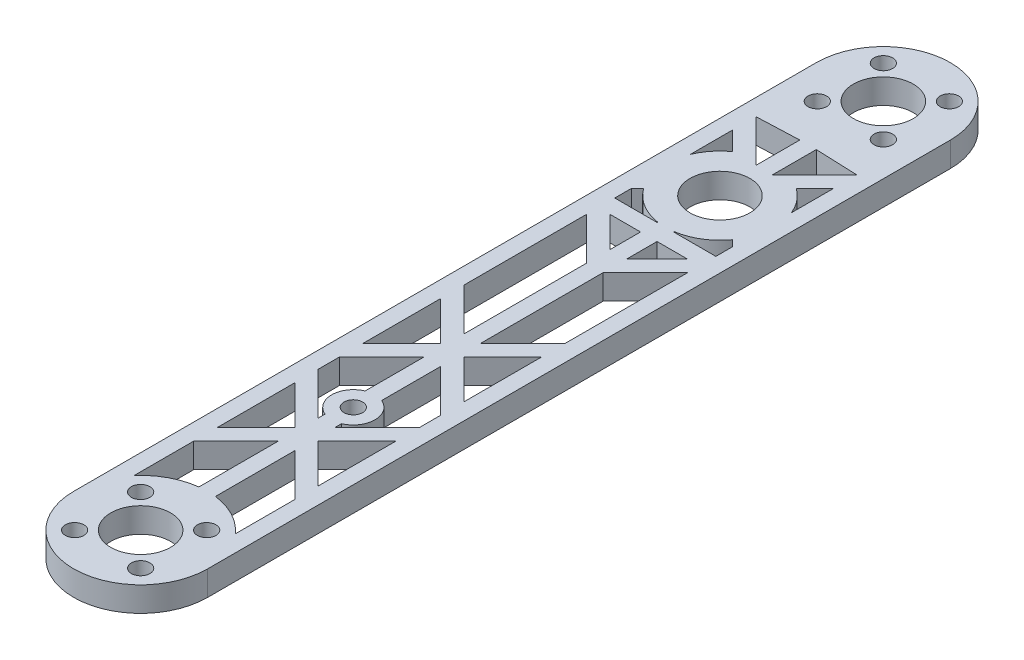
SolidWorks part; units mm, degrees
ref_plane "Front Plane" through (0, 0, 0) normal (0, 0, 1) x (1, 0, 0)
ref_plane "Top Plane" through (0, 0, 0) normal (0, 1, 0) x (1, 0, 0)
ref_plane "Right Plane" through (0, 0, 0) normal (1, 0, 0) x (0, 0, -1)
sketch "Sketch2" plane through (0, 0, 0) normal (0, 1, 0) x (1, 0, 0)
  line L0 (0, 0) -> (-127946.3425, 0) construction
  line L1 (0, 0) -> (0, 127946.3425) construction
  line L2 (-16.25, 90) -> (-16.25, -90)
  line L3 (16.25, 90) -> (16.25, -90)
  line L4 (-20.25, 90) -> (-20.25, -90) construction
  line L5 (8, 82) -> (-8, 82) construction
  line L6 (8, 82) -> (8, 98) construction
  line L7 (8, 98) -> (-8, 98) construction
  line L8 (-8, 82) -> (-8, 98) construction
  line L9 (0, 98) -> (0, 82) construction
  line L10 (8, 90) -> (-8, 90) construction
  line L11 (-8, -82) -> (8, -82) construction
  line L12 (-8, -82) -> (-8, -98) construction
  line L13 (-8, -98) -> (8, -98) construction
  line L14 (8, -82) -> (8, -98) construction
  line L15 (0, -98) -> (0, -82) construction
  line L16 (-8, -90) -> (8, -90) construction
  line L17 (20.25, 90) -> (20.25, -90) construction
  line L18 (-12.25, 90) -> (-12.25, -90) construction
  line L19 (12.25, 90) -> (12.25, -90) construction
  line L20 (-28.9926, 9.1528) -> (49971.0074, 9.1528) construction
  line L21 (-11, 60.9028) -> (11, 60.9028) construction
  line L22 (-11, 60.9028) -> (-11, 16.9028) construction
  line L23 (-11, 16.9028) -> (11, 16.9028) construction
  line L24 (11, 60.9028) -> (11, 16.9028) construction
  line L25 (0, 16.9028) -> (0, 60.9028) construction
  line L26 (-11, 38.9028) -> (11, 38.9028) construction
  line L27 (-5, 63.6528) -> (5, 63.6528) construction
  line L28 (-5, 63.6528) -> (-5, 14.1528) construction
  line L29 (-5, 14.1528) -> (5, 14.1528) construction
  line L30 (5, 63.6528) -> (5, 14.1528) construction
  line L31 (0, 14.1528) -> (0, 63.6528) construction
  line L32 (-5, 38.9028) -> (5, 38.9028) construction
  line L33 (0, 73.75) -> (50000, 73.75) construction
  line L34 (-42.0204, -73.75) -> (49957.9796, -73.75) construction
  line L35 (20.7937, 17.6965) -> (-35334.5454, -35337.6426) construction
  line L36 (-202.4933, 164.0408) -> (35152.6914, -35191.1439) construction
  line L37 (-152.696, 149.5988) -> (35202.4887, -35205.5859) construction
  line L38 (-24.1771, -62.6297) -> (35331.162, 35292.7094) construction
  line L39 (-198.3624, 124.5545) -> (35156.9767, -35230.7846) construction
  line L40 (-34.0458, -107.8537) -> (35321.2932, 35247.4854) construction
  line L41 (-199.7766, 123.1402) -> (35155.5625, -35232.1988) construction
  line L42 (-203.9075, 162.6266) -> (35151.2772, -35192.5581) construction
  line L43 (-154.1102, 148.1846) -> (35201.0745, -35207.0001) construction
  line L44 (19.3795, 19.1107) -> (-35335.9596, -35336.2284) construction
  line L45 (-22.7629, -64.0439) -> (35332.5762, 35291.2952) construction
  line L46 (-32.6316, -109.2679) -> (35322.7075, 35246.0711) construction
  line L47 (-28.9926, 7.1528) -> (49971.0074, 7.1528) construction
  line L48 (-42.0204, -75.75) -> (49957.9796, -75.75) construction
  line L49 (-196.9481, 125.9687) -> (35158.3909, -35229.3704) construction
  line L50 (-201.0791, 165.455) -> (35154.1056, -35189.7297) construction
  line L51 (-151.2818, 151.013) -> (35203.9029, -35204.1717) construction
  line L52 (22.2079, 16.2823) -> (-35333.1312, -35339.0568) construction
  line L53 (-25.5913, -61.2154) -> (35329.7477, 35294.1236) construction
  line L54 (-35.46, -106.4395) -> (35319.879, 35248.8996) construction
  line L55 (-28.9926, 11.1528) -> (49971.0074, 11.1528) construction
  line L56 (-42.0204, -71.75) -> (49957.9796, -71.75) construction
  line L57 (2, 0) -> (2, 127946.3425) construction
  line L58 (-2, 0) -> (-2, 127946.3425) construction
  line L64 (19.0801, 49.5321) -> (12.6868, -90.5789) construction
  line L65 (-12.6868, -90.5789) -> (-19.0801, 49.5321) construction
  circle A0 centre (0, 90) radius 7.25
  circle A1 centre (0, -90) radius 7.25
  arc A2 (16.25, 90) -> (-16.25, 90) centre (0, 90) ccw
  arc A3 (-16.25, -90) -> (16.25, -90) centre (0, -90) ccw
  circle A4 centre (8, 98) radius 2.25
  circle A5 centre (-8, 98) radius 2.25
  circle A6 centre (-8, 82) radius 2.25
  circle A7 centre (8, 82) radius 2.25
  circle A8 centre (8, -98) radius 2.25
  circle A9 centre (8, -82) radius 2.25
  circle A10 centre (-8, -82) radius 2.25
  circle A11 centre (-8, -98) radius 2.25
  arc A12 (-20.25, -90) -> (20.25, -90) centre (0, -90) ccw construction
  arc A13 (20.25, 90) -> (-20.25, 90) centre (0, 90) ccw construction
  arc A14 (-12.25, -90) -> (12.25, -90) centre (0, -90) ccw construction
  arc A15 (12.25, 90) -> (-12.25, 90) centre (0, 90) ccw construction
  arc A16 (-16.25, 90) -> (16.25, 90) centre (0, 90) ccw construction
  circle A17 centre (-5, 63.6528) radius 2.25 construction
  circle A18 centre (5, 63.6528) radius 2.25 construction
  circle A19 centre (-5, 14.1528) radius 2.25 construction
  circle A20 centre (5, 14.1528) radius 2.25 construction
  circle A21 centre (0, 50.4028) radius 7.25
  arc A22 (-16.25, -90) -> (16.25, -90) centre (0, -90) cw construction
  circle A23 centre (0, 50.4028) radius 19.1 construction
  circle A24 centre (0, -90) radius 12.7 construction
  arc A25 (-19.0801, 49.5321) -> (19.0801, 49.5321) centre (0, 50.4028) cw construction
  arc A26 (-12.6868, -90.5789) -> (12.6868, -90.5789) centre (0, -90) ccw construction
  circle A27 centre (0, -38.4526) radius 2.25
  point P16 (0, -90)
  point P29 (0, 38.9028)
  point P42 (0, 38.9028)
  point P59 (0, 73.75)
  point P63 (-12.25, 9.1528)
  point P64 (12.25, 9.1528)
  dimension "D3" = 14.5
  dimension "D4" = 32.5
  dimension "D7" = 4.5
  dimension "D12" = 4.5
  dimension "D14" = 14.5
  dimension "D25" = 25.4
  dimension "D26" = 38.2
  dimension "D28" = 4.5
  dimension "D6" = 16
  dimension "D1" = 90
  dimension "D8" = 22
  dimension "D9" = 44
  dimension "D10" = 10
  dimension "D11" = 49.5
  dimension "D13" = 13.25
  dimension "D15" = 5
  dimension "D16" = 45
  dimension "D17" = 25
  dimension "D18" = 25
  dimension "D19" = 25
  dimension "D20" = 25
  dimension "D2" = 4
  dimension "D5" = 4
  dimension "D21" = 2
  dimension "D22" = 2
  dimension "D23" = 2
  dimension "D24" = 2
extrude "Boss-Extrude1" add sketch "Sketch2" along normal blind 6
sketch "Sketch3" plane through (0, 6, 0) normal (0, 1, 0) x (1, 0, 0)
  line L0 (0, 0) -> (50000, 0) construction
  line L1 (0, 0) -> (0, 50000) construction
  line L2 (2.9662, 90) -> (50002.9662, 90) construction
  line L3 (2.6055, -90) -> (50002.6055, -90) construction
  line L4 (16.25, 44.2284) -> (16.25, 50044.2284) construction
  line L5 (0, -75.75) -> (50000, -75.75) construction
  line L6 (-16.25, 67.8715) -> (-16.25, 50067.8715) construction
  line L7 (2.6055, -92) -> (50002.6055, -92) construction
  line L8 (0, -73.75) -> (50000, -73.75) construction
  line L9 (0, 73.75) -> (50000, 73.75) construction
  line L10 (16.25, -90) -> (16.25, 90) construction
  line L11 (-16.25, 90) -> (-16.25, -90) construction
  line L12 (2, 0) -> (2, 50000) construction
  line L13 (0, -2) -> (50000, -2) construction
  line L14 (0, -71.75) -> (50000, -71.75) construction
  line L15 (2.6055, -88) -> (50002.6055, -88) construction
  line L16 (-2, 0) -> (-2, 50000) construction
  line L17 (0, 2) -> (50000, 2) construction
  line L18 (2.9662, 88) -> (50002.9662, 88) construction
  line L19 (0, 71.75) -> (50000, 71.75) construction
  line L20 (2.9662, 92) -> (50002.9662, 92) construction
  line L21 (0, 75.75) -> (50000, 75.75) construction
  line L22 (-12.25, 67.8715) -> (-12.25, 50067.8715) construction
  line L23 (20.25, 44.2284) -> (20.25, 50044.2284) construction
  line L24 (-20.25, 67.8715) -> (-20.25, 50067.8715) construction
  line L25 (12.25, 44.2284) -> (12.25, 50044.2284) construction
  line L26 (-29.0229, 35.1528) -> (49970.9771, 35.1528) construction
  line L27 (-29.0229, 33.1528) -> (49970.9771, 33.1528) construction
  line L28 (-29.0229, 37.1528) -> (49970.9771, 37.1528) construction
  line L29 (-2.2407, 23.1435) -> (35353.0984, -35332.1956) construction
  line L30 (2.2407, 23.1435) -> (-35353.0984, -35332.1956) construction
  line L31 (-27.3527, 12.9001) -> (35327.9864, -35342.4389) construction
  line L32 (-42.8074, -7.0005) -> (35312.5316, -35362.3395) construction
  line L33 (25.8207, 82.0788) -> (-35329.5183, -35273.2602) construction
  line L34 (119.5819, 105.1293) -> (-35235.7572, -35250.2097) construction
  line L35 (78.8149, -22.5568) -> (-35276.5242, 35332.7823) construction
  line L36 (-113.2525, -163.0604) -> (35242.0865, 35192.2786) construction
  line L37 (24.4065, 83.4931) -> (-35330.9325, -35271.846) construction
  line L38 (0.8265, 24.5577) -> (-35354.5126, -35330.7814) construction
  line L39 (118.1677, 106.5435) -> (-35237.1714, -35248.7955) construction
  line L40 (-111.8383, -164.4746) -> (35243.5008, 35190.8644) construction
  line L41 (80.2291, -21.1425) -> (-35275.11, 35334.1965) construction
  line L42 (-3.6549, 21.7292) -> (35351.6842, -35333.6098) construction
  line L43 (-28.7669, 11.4859) -> (35326.5722, -35343.8531) construction
  line L44 (-44.2216, -8.4147) -> (35311.1174, -35363.7537) construction
  line L45 (27.2349, 80.6646) -> (-35328.1041, -35274.6744) construction
  line L46 (3.6549, 21.7292) -> (-35351.6842, -35333.6098) construction
  line L47 (120.9961, 103.7151) -> (-35234.343, -35251.6239) construction
  line L48 (-114.6667, -161.6462) -> (35240.6723, 35193.6929) construction
  line L49 (77.4007, -23.971) -> (-35277.9384, 35331.3681) construction
  line L50 (-0.8265, 24.5577) -> (35354.5126, -35330.7814) construction
  line L51 (-25.9385, 14.3144) -> (35329.4006, -35341.0247) construction
  line L52 (-41.3932, -5.5863) -> (35313.9459, -35360.9253) construction
  line L57 (-12.25, 30.3244) -> (-2, 20.0744)
  line L58 (-2, 20.0744) -> (-2, -9.6241)
  line L59 (-2, -9.6241) -> (-12.25, 0.6259)
  line L60 (-12.25, 0.6259) -> (-12.25, 30.3244)
  line L61 (-12.25, -5.031) -> (-12.25, -23.8741)
  line L62 (-12.25, -23.8741) -> (-2.8284, -14.4526)
  line L63 (-2.8284, -14.4526) -> (-12.25, -5.031)
  line L64 (-9.4216, 33.1528) -> (-2, 33.1528)
  line L67 (-2, 25.7312) -> (-9.4216, 33.1528)
  line L71 (12.25, -23.8741) -> (2.8284, -14.4526)
  line L72 (12.25, -5.031) -> (12.25, -23.8741)
  line L73 (2.8284, -14.4526) -> (12.25, -5.031)
  line L76 (9.4216, 33.1528) -> (2, 33.1528)
  line L77 (2, 25.7312) -> (9.4216, 33.1528)
  line L78 (2, -9.6241) -> (12.25, 0.6259)
  line L79 (2, 20.0744) -> (2, -9.6241)
  line L80 (12.25, 30.3244) -> (2, 20.0744)
  line L81 (12.25, 0.6259) -> (12.25, 30.3244)
  line L82 (2, 25.7312) -> (2, 33.1528)
  line L83 (-2, 33.1528) -> (-2, 25.7312)
  line L84 (-12.25, 71.3366) -> (-2, 61.0866)
  line L85 (-2, 61.0866) -> (-2, 71.75)
  line L86 (-2, 71.75) -> (-12.25, 71.3366)
  line L87 (-12.25, 65.6797) -> (-12.25, 55.4525)
  line L88 (-12.25, 65.6797) -> (-7.7327, 61.1624)
  line L89 (-12.25, 41.1797) -> (-12.25, 37.1528)
  line L90 (-12.25, 37.1528) -> (-2, 37.1528)
  line L91 (-2, 37.1528) -> (-2, 37.3046)
  line L92 (-12.25, 41.1797) -> (-10.7596, 42.6701)
  line L93 (12.25, 41.1797) -> (12.25, 37.1528)
  line L94 (12.25, 37.1528) -> (2, 37.1528)
  line L95 (2, 37.1528) -> (2, 37.3046)
  line L96 (12.25, 41.1797) -> (10.7596, 42.6701)
  line L97 (12.25, 65.6797) -> (7.7327, 61.1624)
  line L98 (12.25, 65.6797) -> (12.25, 55.4525)
  line L99 (2, 61.0866) -> (2, 71.75)
  line L100 (12.25, 71.3366) -> (2, 61.0866)
  line L101 (2, 71.75) -> (12.25, 71.3366)
  line L102 (-2, -19.281) -> (-12.25, -29.531)
  line L103 (-12.25, -29.531) -> (-12.25, -34.7295)
  line L104 (-12.25, -34.7295) -> (-2, -44.9795)
  line L106 (-12.25, -40.3863) -> (-12.25, -59.2295)
  line L107 (-12.25, -59.2295) -> (-2.8284, -49.8079)
  line L108 (-2.8284, -49.8079) -> (-12.25, -40.3863)
  line L109 (-2, -54.6363) -> (-12.25, -64.8863)
  line L110 (-12.25, -64.8863) -> (-12.25, -79.3229)
  line L112 (-2, -73.8735) -> (-2, -54.6363)
  line L114 (12.25, -64.8863) -> (12.25, -79.3229)
  line L115 (2, -54.6363) -> (12.25, -64.8863)
  line L116 (2, -73.8735) -> (2, -54.6363)
  line L117 (12.25, -59.2295) -> (2.8284, -49.8079)
  line L118 (12.25, -40.3863) -> (12.25, -59.2295)
  line L119 (2.8284, -49.8079) -> (12.25, -40.3863)
  line L120 (12.25, -34.7295) -> (2, -44.9795)
  line L121 (12.25, -29.531) -> (12.25, -34.7295)
  line L122 (2, -19.281) -> (12.25, -29.531)
  line L124 (-2, -44.9795) -> (-2, -43.3067)
  line L125 (-2, -19.281) -> (-2, -33.5984)
  line L126 (2, -44.9795) -> (2, -43.3067)
  line L127 (2, -19.281) -> (2, -33.5984)
  circle A0 centre (0, 90) radius 16.25 construction
  circle A1 centre (0, -90) radius 16.25 construction
  arc A2 (16.25, 90) -> (-16.25, 90) centre (0, 90) ccw construction
  arc A3 (-2, -33.5984) -> (-2, -43.3067) centre (0, -38.4526) ccw
  circle A6 centre (0, 50.4028) radius 7.25 construction
  circle A7 centre (0, 50.4028) radius 7.25 construction
  circle A8 centre (0, 50.4028) radius 13.25 construction
  arc A9 (-7.7327, 61.1624) -> (-12.25, 55.4525) centre (0, 50.4028) ccw
  arc A10 (-10.7596, 42.6701) -> (-2, 37.3046) centre (0, 50.4028) ccw
  arc A11 (10.7596, 42.6701) -> (2, 37.3046) centre (0, 50.4028) cw
  arc A12 (7.7327, 61.1624) -> (12.25, 55.4525) centre (0, 50.4028) cw
  arc A13 (2, -33.5984) -> (2, -43.3067) centre (0, -38.4526) cw
  arc A14 (-12.25, -79.3229) -> (-2, -73.8735) centre (0, -90) cw
  circle A15 centre (0, -38.4526) radius 5.25
  circle A16 centre (0, -38.4526) radius 5.25 construction
  arc A17 (12.25, -79.3229) -> (2, -73.8735) centre (0, -90) ccw
  point P70 (-12.25, 33.1528)
  point P71 (12.25, 33.1528)
  dimension "D5" = 4
  dimension "D10" = 25
  dimension "D11" = 25
  dimension "D12" = 25
  dimension "D13" = 25
  dimension "D14" = 135
  dimension "D15" = 25
  dimension "D16" = 25
  dimension "D1" = 2
  dimension "D2" = 2
  dimension "D3" = 2
  dimension "D4" = 2
  dimension "D6" = 4
  dimension "D8" = 2
  dimension "D9" = 2
  dimension "D17" = 2
  dimension "D18" = 2
  dimension "D7" = 6
  dimension "D19" = 3
extrude "Cut-Extrude1" cut sketch "Sketch3" against normal blind 6
equation "\"pocketing\"= 2mm'hole"
equation "\"D5@Sketch2\"=\"pocketing\"*2"
equation "\"D2@Sketch2\"=\"pocketing\"*2"
equation "\"D24@Sketch2\"=\"pocketing\""
equation "\"D23@Sketch2\"=\"pocketing\""
equation "\"D22@Sketch2\"=\"pocketing\""
equation "\"D21@Sketch2\"=\"pocketing\""
equation "\"D5@Sketch3\"=\"pocketing\"*2"
equation "\"D6@Sketch3\"=\"pocketing\"*2"
equation "\"D2@Sketch3\"=\"pocketing\""
equation "\"D1@Sketch3\"=\"pocketing\""
equation "\"D18@Sketch3\"=\"pocketing\""
equation "\"D17@Sketch3\"=\"pocketing\""
equation "\"D9@Sketch3\"=\"pocketing\""
equation "\"D8@Sketch3\"=\"pocketing\""
equation "\"D4@Sketch3\"=\"pocketing\""
equation "\"D3@Sketch3\"=\"pocketing\""
